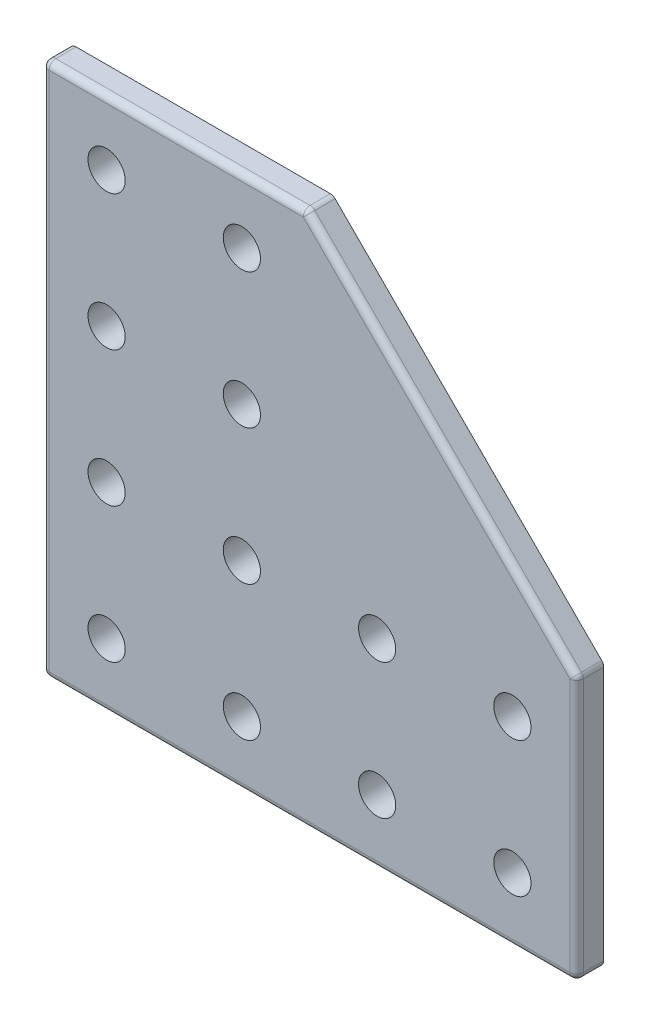
SolidWorks part; units mm, degrees
ref_plane "Front Plane" through (0, 0, 0) normal (0, 0, 1) x (1, 0, 0)
ref_plane "Top Plane" through (0, 0, 0) normal (0, 1, 0) x (1, 0, 0)
ref_plane "Right Plane" through (0, 0, 0) normal (1, 0, 0) x (0, 0, -1)
sketch "Sketch1" plane through (0, 0, 0) normal (0, 0, 1) x (1, 0, 0)
  line L0 (0, 0) -> (0, 79)
  line L1 (9.5, 9.5) -> (29.5, 9.5) construction
  line L2 (29.5, 9.5) -> (49.5, 9.5) construction
  line L3 (9.5, 9.5) -> (9.5, 29.5) construction
  line L4 (39, 79) -> (0, 79)
  line L5 (79, 0) -> (0, 0)
  line L6 (9.5, 29.5) -> (9.5, 49.5) construction
  line L7 (79, 39) -> (79, 0)
  line L8 (39, 79) -> (79, 39)
  line L9 (19.5, 69.5) -> (19.5, 79) construction
  line L10 (79, 19.5) -> (69.5, 19.5) construction
  line L11 (29.5, 9.5) -> (29.5, 29.5) construction
  line L12 (9.5, 69.5) -> (9.5, 49.5) construction
  line L13 (29.5, 29.5) -> (29.5, 49.5) construction
  line L14 (29.5, 49.5) -> (29.5, 69.5) construction
  line L15 (29.5, 69.5) -> (9.5, 69.5) construction
  line L16 (29.5, 49.5) -> (9.5, 49.5) construction
  line L17 (29.5, 29.5) -> (9.5, 29.5) construction
  line L18 (29.5, 29.5) -> (49.5, 29.5) construction
  line L19 (49.5, 29.5) -> (49.5, 9.5) construction
  line L20 (69.5, 9.5) -> (69.5, 29.5) construction
  line L21 (69.5, 29.5) -> (49.5, 29.5) construction
  line L23 (69.5, 9.5) -> (49.5, 9.5) construction
  circle A0 centre (9.5, 9.5) radius 2.75
  circle A1 centre (29.5, 9.5) radius 2.75
  circle A2 centre (49.5, 9.5) radius 2.75
  circle A3 centre (9.5, 29.5) radius 2.75
  circle A4 centre (9.5, 49.5) radius 2.75
  circle A5 centre (69.5, 9.5) radius 2.75
  circle A6 centre (69.5, 29.5) radius 2.75
  circle A7 centre (49.5, 29.5) radius 2.75
  circle A8 centre (29.5, 29.5) radius 2.75
  circle A9 centre (29.5, 49.5) radius 2.75
  circle A10 centre (29.5, 69.5) radius 2.75
  circle A11 centre (9.5, 69.5) radius 2.75
  dimension "D1" = 20
  dimension "E" = 5.5
  dimension "D2" = 9.5
  dimension "C" = 79
  dimension "D3" = 20
  dimension "B" = 79
  dimension "D4" = 9.5
extrude "Boss-Extrude1" add sketch "Sketch1" along normal mid plane 4
fillet "Fillet1" radius 1 10 edges at (0, 0, 0) (0, 39.5, 2) (39.5, 0, 2) (79, 19.5, 2) (79, 0, 0) (19.5, 79, 2) (0, 79, 0) (59, 59, 2) (79, 39, 0) (39, 79, 0)
